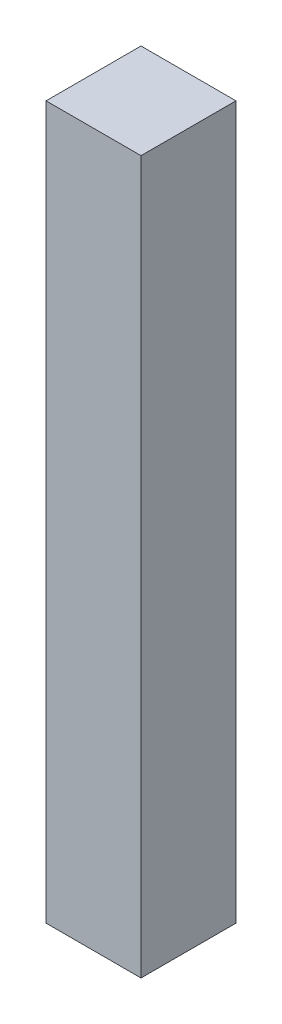
SolidWorks part; units mm, degrees
ref_plane "Спереди" through (0, 0, 0) normal (0, 0, 1) x (1, 0, 0)
ref_plane "Сверху" through (0, 0, 0) normal (0, 1, 0) x (1, 0, 0)
ref_plane "Справа" through (0, 0, 0) normal (1, 0, 0) x (0, 0, -1)
other "Configuration Table"
sketch "Эскиз1" plane through (0, 0, 0) normal (0, 1, 0) x (1, 0, 0)
  line L1 (-10, -10) -> (10, -10)
  line L2 (-10, -10) -> (-10, 10)
  line L3 (-10, 10) -> (10, 10)
  line L4 (10, -10) -> (10, 10)
  line L5 (-10, -10) -> (10, 10) construction
  line L6 (-10, 10) -> (10, -10) construction
  point P0 (0, 0)
  dimension "D1" = 20
extrude "Бобышка-Вытянуть1" add sketch "Эскиз1" along normal mid plane 150
